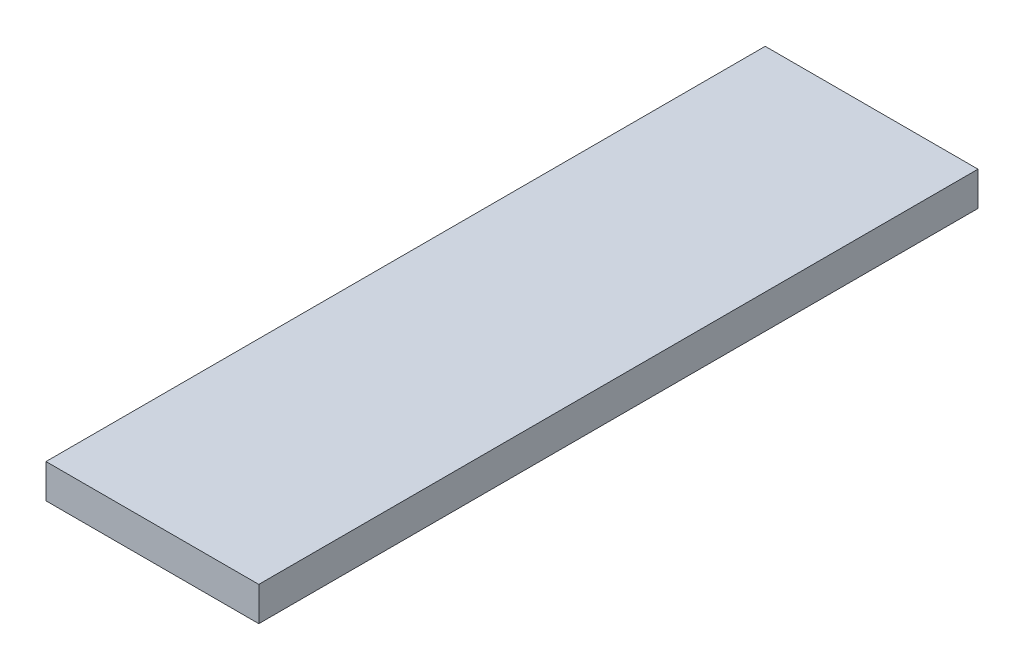
SolidWorks part; units mm, degrees
material "Сосна"
ref_plane "Спереди" through (0, 0, 0) normal (0, 0, 1) x (1, 0, 0)
ref_plane "Сверху" through (0, 0, 0) normal (0, 1, 0) x (1, 0, 0)
ref_plane "Справа" through (0, 0, 0) normal (1, 0, 0) x (0, 0, -1)
sketch "Эскиз1" plane through (0, 0, 0) normal (0, 0, 1) x (1, 0, 0)
  line L1 (0, 0) -> (-200, 0)
  line L2 (0, 0) -> (0, 32)
  line L3 (0, 32) -> (-200, 32)
  line L4 (-200, 0) -> (-200, 32)
  dimension "D1" = 32
  dimension "D2" = 200
extrude "Бобышка-Вытянуть1" add sketch "Эскиз1" along normal up to surface (676 mm away)
